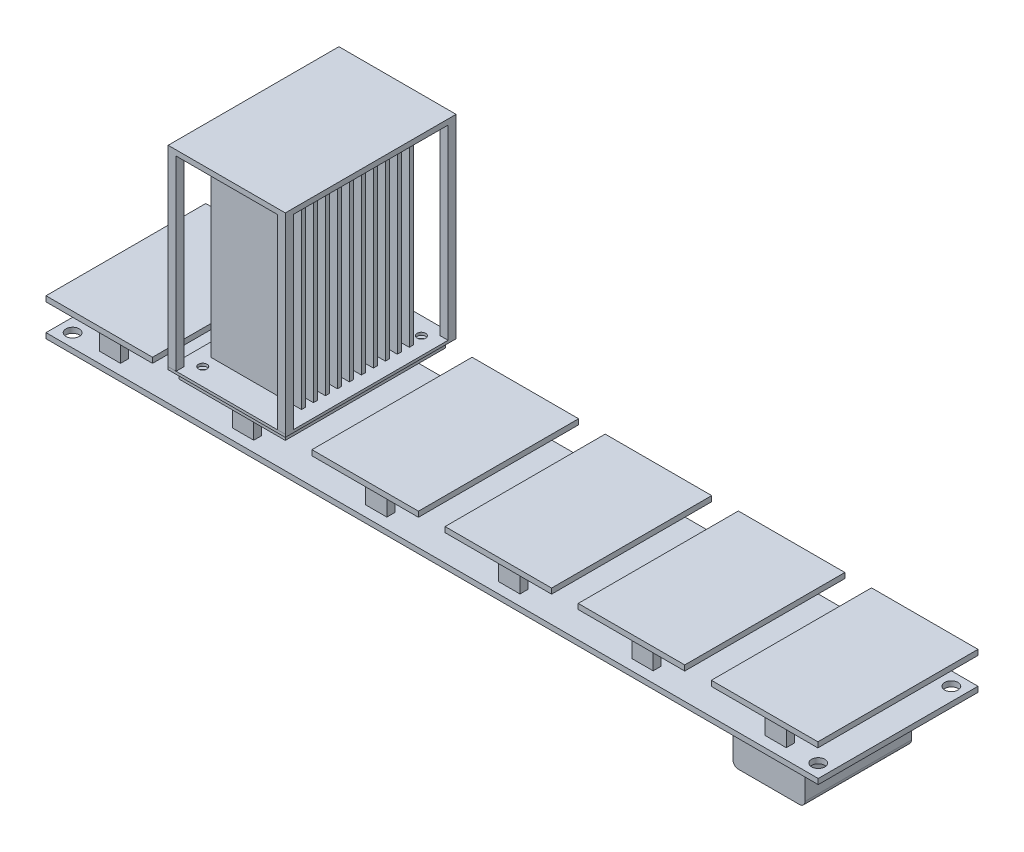
SolidWorks part; units mm, degrees
ref_plane "Ebene vorne" through (0, 0, 0) normal (0, 0, 1) x (1, 0, 0)
ref_plane "Ebene oben" through (0, 0, 0) normal (0, 1, 0) x (1, 0, 0)
ref_plane "Ebene rechts" through (0, 0, 0) normal (1, 0, 0) x (0, 0, -1)
sketch "Skizze1" plane through (0, 0, 0) normal (0, 0, 1) x (1, 0, 0)
  line L1 (0, 0) -> (290, 0)
  line L2 (0, 0) -> (0, 2)
  line L3 (0, 2) -> (290, 2)
  line L4 (290, 0) -> (290, 2)
  dimension "D1" = 290
  dimension "D2" = 2
extrude "Aufsatz-Linear austragen1" add sketch "Skizze1" along normal blind 60
sketch "Skizze2" plane through (0, 2, 0) normal (0, 1, 0) x (1, 0, 0)
  line L0 (290, -60) -> (290, 0) construction
  line L1 (0, -60) -> (0, 0) construction
  line L2 (290, -60) -> (0, -60) construction
  line L3 (290, 0) -> (0, 0) construction
  circle A0 centre (5, -5) radius 2.5
  circle A1 centre (5, -55) radius 2.5
  circle A2 centre (285, -55) radius 2.5
  circle A3 centre (285, -5) radius 2.5
  dimension "D1" = 5
  dimension "D2" = 5
  dimension "D3" = 5
  dimension "D4" = 5
  dimension "D5" = 5
  dimension "D6" = 5
  dimension "D7" = 5
  dimension "D9" = 5
  dimension "D10" = 5
  dimension "D11" = 5
  dimension "D12" = 5
  dimension "D8" = 5
extrude "Schnitt-Linear austragen1" cut sketch "Skizze2" against normal blind 60
sketch "Skizze3" plane through (0, 2, 0) normal (0, 1, 0) x (1, 0, 0)
  line L0 (0, -60) -> (0, 0) construction
  line L1 (16, -5) -> (24, -5)
  line L2 (16, -5) -> (16, -8)
  line L3 (16, -8) -> (24, -8)
  line L4 (24, -5) -> (24, -8)
  line L5 (66, -8) -> (74, -8)
  line L6 (66, -8) -> (66, -5)
  line L7 (66, -5) -> (74, -5)
  line L8 (74, -8) -> (74, -5)
  line L9 (116, -8) -> (124, -8)
  line L10 (116, -8) -> (116, -5)
  line L11 (116, -5) -> (124, -5)
  line L12 (124, -8) -> (124, -5)
  line L13 (166, -8) -> (174, -8)
  line L14 (166, -8) -> (166, -5)
  line L15 (166, -5) -> (174, -5)
  line L16 (174, -8) -> (174, -5)
  line L17 (216, -5) -> (224, -5)
  line L18 (216, -5) -> (216, -8)
  line L19 (216, -8) -> (224, -8)
  line L20 (224, -5) -> (224, -8)
  line L21 (266, -5) -> (274, -5)
  line L22 (266, -5) -> (266, -8)
  line L23 (266, -8) -> (274, -8)
  line L24 (274, -5) -> (274, -8)
  line L33 (266, -56) -> (274, -56)
  line L34 (266, -56) -> (266, -53)
  line L35 (266, -53) -> (274, -53)
  line L36 (274, -56) -> (274, -53)
  line L37 (216, -56) -> (224, -56)
  line L38 (216, -56) -> (216, -53)
  line L39 (216, -53) -> (224, -53)
  line L40 (224, -56) -> (224, -53)
  line L41 (166, -56) -> (174, -56)
  line L42 (166, -56) -> (166, -53)
  line L43 (166, -53) -> (174, -53)
  line L44 (174, -56) -> (174, -53)
  line L45 (116, -56) -> (124, -56)
  line L46 (116, -56) -> (116, -53)
  line L47 (116, -53) -> (124, -53)
  line L48 (124, -56) -> (124, -53)
  line L49 (66, -56) -> (74, -56)
  line L50 (66, -56) -> (66, -53)
  line L51 (66, -53) -> (74, -53)
  line L52 (74, -56) -> (74, -53)
  line L53 (16, -56) -> (24, -56)
  line L54 (16, -56) -> (16, -53)
  line L55 (16, -53) -> (24, -53)
  line L56 (24, -56) -> (24, -53)
  line L58 (290, -60) -> (0, -60) construction
  dimension "D1" = 3
  dimension "D2" = 3
  dimension "D3" = 3
  dimension "D4" = 3
  dimension "D5" = 3
  dimension "D6" = 3
  dimension "D7" = 3
  dimension "D8" = 3
  dimension "D11" = 3
  dimension "D12" = 3
  dimension "D13" = 3
  dimension "D14" = 3
  dimension "D15" = 8
  dimension "D16" = 8
  dimension "D17" = 8
  dimension "D18" = 8
  dimension "D19" = 8
  dimension "D20" = 8
  dimension "D21" = 8
  dimension "D22" = 8
  dimension "D23" = 8
  dimension "D24" = 8
  dimension "D27" = 8
  dimension "D28" = 8
  dimension "D29" = 42
  dimension "D30" = 42
  dimension "D31" = 42
  dimension "D32" = 42
  dimension "D33" = 42
  dimension "D34" = 42
  dimension "D35" = 42
  dimension "D36" = 42
  dimension "D40" = 42
  dimension "D41" = 42
  dimension "D42" = 16
  dimension "D43" = 16
  dimension "D44" = 45
  dimension "D45" = 4
extrude "Aufsatz-Linear austragen2" add sketch "Skizze3" along normal blind 10
sketch "Skizze4" plane through (0, 12, 0) normal (0, 1, 0) x (1, 0, 0)
  line L1 (0, 0) -> (40, 0)
  line L2 (0, 0) -> (0, -60)
  line L3 (0, -60) -> (40, -60)
  line L4 (40, 0) -> (40, -60)
  line L5 (50, 0) -> (90, 0)
  line L6 (50, 0) -> (50, -60.1338)
  line L7 (50, -60.1338) -> (90, -60.1338)
  line L8 (90, 0) -> (90, -60.1338)
  line L9 (100, -60.1338) -> (140, -60.1338)
  line L10 (100, -60.1338) -> (100, 0)
  line L11 (100, 0) -> (140, 0)
  line L12 (140, -60.1338) -> (140, 0)
  line L13 (150, 0) -> (190, 0)
  line L14 (150, 0) -> (150, -60.1338)
  line L15 (150, -60.1338) -> (190, -60.1338)
  line L16 (190, 0) -> (190, -60.1338)
  line L17 (200, -60.1338) -> (240, -60.1338)
  line L18 (200, -60.1338) -> (200, 0)
  line L19 (200, 0) -> (240, 0)
  line L20 (240, -60.1338) -> (240, 0)
  line L21 (250, 0) -> (290, 0)
  line L22 (250, 0) -> (250, -60.1338)
  line L23 (250, -60.1338) -> (290, -60.1338)
  line L24 (290, 0) -> (290, -60.1338)
  dimension "D1" = 40
  dimension "D2" = 60
  dimension "D3" = 10
  dimension "D4" = 40
  dimension "D5" = 10
  dimension "D6" = 40
  dimension "D7" = 10
  dimension "D8" = 40
  dimension "D9" = 10
  dimension "D10" = 40
  dimension "D12" = 40
  dimension "D14" = 10
extrude "Aufsatz-Linear austragen3" add sketch "Skizze4" along normal blind 2
sketch "Skizze6" plane through (0, 14, 0) normal (0, 1, 0) x (1, 0, 0)
  line L1 (50, 0) -> (90, 0)
  line L2 (50, 0) -> (50, -60.1338)
  line L3 (50, -60.1338) -> (90, -60.1338)
  line L4 (90, 0) -> (90, -60.1338)
extrude "Aufsatz-Linear austragen4" add sketch "Skizze6" along normal blind 2
sketch "Skizze7" plane through (90, 0, 0) normal (1, 0, 0) x (0, 0, -1)
  line L0 (-60.1338, 16) -> (-60.1338, 12) construction
  line L1 (0, 16) -> (-60.1338, 16)
  line L2 (0, 16) -> (0, 14)
  line L3 (0, 14) -> (-60.1338, 14)
  line L4 (-60.1338, 16) -> (-60.1338, 14)
  dimension "D1" = 2
extrude "Aufsatz-Linear austragen5" add sketch "Skizze7" along normal blind 2
sketch "Skizze8" plane through (50, 0, 0) normal (-1, 0, 0) x (0, 0, 1)
  line L0 (60.1338, 16) -> (60.1338, 12) construction
  line L1 (0, 16) -> (60.1338, 16)
  line L2 (0, 16) -> (0, 14)
  line L3 (0, 14) -> (60.1338, 14)
  line L4 (60.1338, 16) -> (60.1338, 14)
  dimension "D1" = 2
extrude "Aufsatz-Linear austragen6" add sketch "Skizze8" along normal blind 2
sketch "Skizze9" plane through (0, 0, 60.1338) normal (0, 0, 1) x (1, 0, 0)
  line L1 (48, 16) -> (92, 16)
  line L2 (48, 16) -> (48, 14)
  line L3 (48, 14) -> (92, 14)
  line L4 (92, 16) -> (92, 14)
extrude "Aufsatz-Linear austragen7" add sketch "Skizze9" along normal blind 2
sketch "Skizze10" plane through (0, 0, 0) normal (0, 0, -1) x (-1, 0, 0)
  line L1 (-92, 16) -> (-48, 16)
  line L2 (-92, 16) -> (-92, 14)
  line L3 (-92, 14) -> (-48, 14)
  line L4 (-48, 16) -> (-48, 14)
extrude "Aufsatz-Linear austragen8" add sketch "Skizze10" along normal blind 2
sketch "Skizze11" plane through (0, 16, 0) normal (0, 1, 0) x (1, 0, 0)
  line L0 (48, -62.1338) -> (48, 2) construction
  line L1 (53, -9.065) -> (87, -9.065)
  line L2 (53, -9.065) -> (53, -10.565)
  line L3 (53, -10.565) -> (87, -10.565)
  line L4 (87, -9.065) -> (87, -10.565)
  line L5 (53, -13.565) -> (87, -13.565)
  line L6 (53, -13.565) -> (53, -15.065)
  line L7 (53, -15.065) -> (87, -15.065)
  line L8 (87, -13.565) -> (87, -15.065)
  line L9 (53, -18.065) -> (87, -18.065)
  line L10 (53, -18.065) -> (53, -19.565)
  line L11 (53, -19.565) -> (87, -19.565)
  line L12 (87, -18.065) -> (87, -19.565)
  line L13 (53, -22.565) -> (87, -22.565)
  line L14 (53, -22.565) -> (53, -24.065)
  line L15 (53, -24.065) -> (87, -24.065)
  line L16 (87, -22.565) -> (87, -24.065)
  line L17 (53, -27.065) -> (87, -27.065)
  line L18 (53, -27.065) -> (53, -28.565)
  line L19 (53, -28.565) -> (87, -28.565)
  line L20 (87, -27.065) -> (87, -28.565)
  line L21 (53, -31.565) -> (87, -31.565)
  line L22 (53, -31.565) -> (53, -33.065)
  line L23 (53, -33.065) -> (87, -33.065)
  line L24 (87, -31.565) -> (87, -33.065)
  line L25 (53, -36.065) -> (87, -36.065)
  line L26 (53, -36.065) -> (53, -37.565)
  line L27 (53, -37.565) -> (87, -37.565)
  line L28 (87, -36.065) -> (87, -37.565)
  line L29 (53, -40.565) -> (87, -40.565)
  line L30 (53, -40.565) -> (53, -42.065)
  line L31 (53, -42.065) -> (87, -42.065)
  line L32 (87, -40.565) -> (87, -42.065)
  line L33 (53, -45.065) -> (87, -45.065)
  line L34 (53, -45.065) -> (53, -46.565)
  line L35 (53, -46.565) -> (87, -46.565)
  line L36 (87, -45.065) -> (87, -46.565)
  line L37 (53, -49.565) -> (87, -49.565)
  line L38 (53, -49.565) -> (53, -51.065)
  line L39 (53, -51.065) -> (87, -51.065)
  line L40 (87, -49.565) -> (87, -51.065)
  line L41 (92, 2) -> (92, -62.1338) construction
  line L45 (48, 2) -> (92, 2) construction
  dimension "D1" = 1.5
  dimension "D2" = 1.5
  dimension "D3" = 1.5
  dimension "D4" = 1.5
  dimension "D5" = 1.5
  dimension "D6" = 1.5
  dimension "D7" = 1.5
  dimension "D8" = 1.5
  dimension "D9" = 1.5
  dimension "D10" = 1.5
  dimension "D11" = 5
  dimension "D12" = 5
  dimension "D13" = 5
  dimension "D14" = 5
  dimension "D15" = 5
  dimension "D16" = 5
  dimension "D17" = 5
  dimension "D18" = 5
  dimension "D19" = 5
  dimension "D20" = 5
  dimension "D21" = 5
  dimension "D22" = 5
  dimension "D23" = 5
  dimension "D24" = 5
  dimension "D25" = 5
  dimension "D26" = 5
  dimension "D27" = 5
  dimension "D28" = 5
  dimension "D29" = 5
  dimension "D30" = 34
  dimension "D31" = 3
  dimension "D32" = 11.065
  dimension "D33" = 3
  dimension "D34" = 3
  dimension "D35" = 3
  dimension "D36" = 3
  dimension "D37" = 3
  dimension "D38" = 3
  dimension "D39" = 3
  dimension "D40" = 3
  dimension "D41" = 34
extrude "Aufsatz-Linear austragen9" add sketch "Skizze11" along normal blind 70
sketch "Skizze12" plane through (0, 0, 62.1338) normal (0, 0, 1) x (1, 0, 0)
  line L0 (92, 14) -> (92, 16) construction
  line L1 (48, 14) -> (92, 14)
  line L2 (48, 14) -> (48, 15)
  line L3 (48, 15) -> (92, 15)
  line L4 (92, 14) -> (92, 15)
extrude "Schnitt-Linear austragen3" cut sketch "Skizze12" against normal blind 70
sketch "Skizze13" plane through (0, 86, 0) normal (0, 1, 0) x (1, 0, 0)
  line L0 (53, -51.065) -> (87, -51.065) construction
  line L1 (48, 2) -> (92, 2)
  line L2 (48, 2) -> (48, -62.13)
  line L3 (48, -62.13) -> (92, -62.13)
  line L4 (92, 2) -> (92, -62.13)
  line L5 (48, 2) -> (92, 2) construction
  line L6 (92, 2) -> (92, -62.1338) construction
  line L7 (48, -62.1338) -> (48, 2) construction
  dimension "D1" = 11.065
  dimension "D2" = 0
  dimension "D3" = 0
  dimension "D4" = 0
  dimension "D5" = 0
extrude "Aufsatz-Linear austragen10" add sketch "Skizze13" along normal blind 2
sketch "Skizze14" plane through (0, 88, 0) normal (0, 1, 0) x (1, 0, 0)
  line L1 (48, 2) -> (51, 2)
  line L2 (48, 2) -> (48, -1)
  line L3 (48, -1) -> (51, -1)
  line L4 (51, 2) -> (51, -1)
  line L5 (92, 2) -> (89, 2)
  line L6 (92, 2) -> (92, -1)
  line L7 (92, -1) -> (89, -1)
  line L8 (89, 2) -> (89, -1)
  line L9 (92, -62.13) -> (89, -62.13)
  line L10 (92, -62.13) -> (92, -59.13)
  line L11 (92, -59.13) -> (89, -59.13)
  line L12 (89, -62.13) -> (89, -59.13)
  line L13 (48, -62.13) -> (51, -62.13)
  line L14 (48, -62.13) -> (48, -59.13)
  line L15 (48, -59.13) -> (51, -59.13)
  line L16 (51, -62.13) -> (51, -59.13)
  dimension "D1" = 3
  dimension "D2" = 3
  dimension "D3" = 3
  dimension "D4" = 3
  dimension "D5" = 3
  dimension "D6" = 3
  dimension "D7" = 3
  dimension "D8" = 3
extrude "Aufsatz-Linear austragen11" add sketch "Skizze14" against normal blind 72
sketch "Skizze15" plane through (0, 0, 0) normal (0, -1, 0) x (1, 0, 0)
  line L0 (290, 60) -> (290, 0) construction
  line L1 (248, 50) -> (275, 50)
  line L2 (248, 50) -> (248, 10)
  line L3 (248, 10) -> (275, 10)
  line L4 (275, 50) -> (275, 10)
  line L5 (0, 0) -> (290, 0) construction
  line L6 (0, 60) -> (290, 60) construction
  dimension "D1" = 27
  dimension "D2" = 15
  dimension "D3" = 10
  dimension "D4" = 10
extrude "Aufsatz-Linear austragen12" add sketch "Skizze15" along normal blind 20
fillet "Verrundung2" radius 2 1 edges at (275, -20, 30)
fillet "Verrundung3" radius 2 1 edges at (248, -20, 30)
ref_plane "Ebene14" through (87, 16, 46.565) normal (1, 0, 0) x (0, 0, -1)
sketch "Skizze18" plane through (0, 16, 0) normal (0, 1, 0) x (1, 0, 0)
  line L0 (90, 0) -> (50, 0) construction
  line L3 (50, -60.1338) -> (90, -60.1338) construction
  line L6 (90, -60.1338) -> (90, 0) construction
  line L7 (50, 0) -> (50, -60.1338) construction
  circle A0 centre (54.5, -4.5) radius 1.6
  circle A1 centre (54.5, -55.6338) radius 1.6
  circle A2 centre (85.5, -55.6338) radius 1.6
  circle A3 centre (85.5, -4.5) radius 1.6
  dimension "D1" = 3.2
  dimension "D2" = 3.2
  dimension "D3" = 3.2
  dimension "D4" = 3.2
  dimension "D5" = 4.5
  dimension "D6" = 4.5
  dimension "D7" = 4.5
  dimension "D8" = 4.5
  dimension "D9" = 4.5
  dimension "D10" = 4.5
  dimension "D11" = 4.5
  dimension "D12" = 4.5
extrude "Schnitt-Linear austragen4" cut sketch "Skizze18" against normal blind 10
